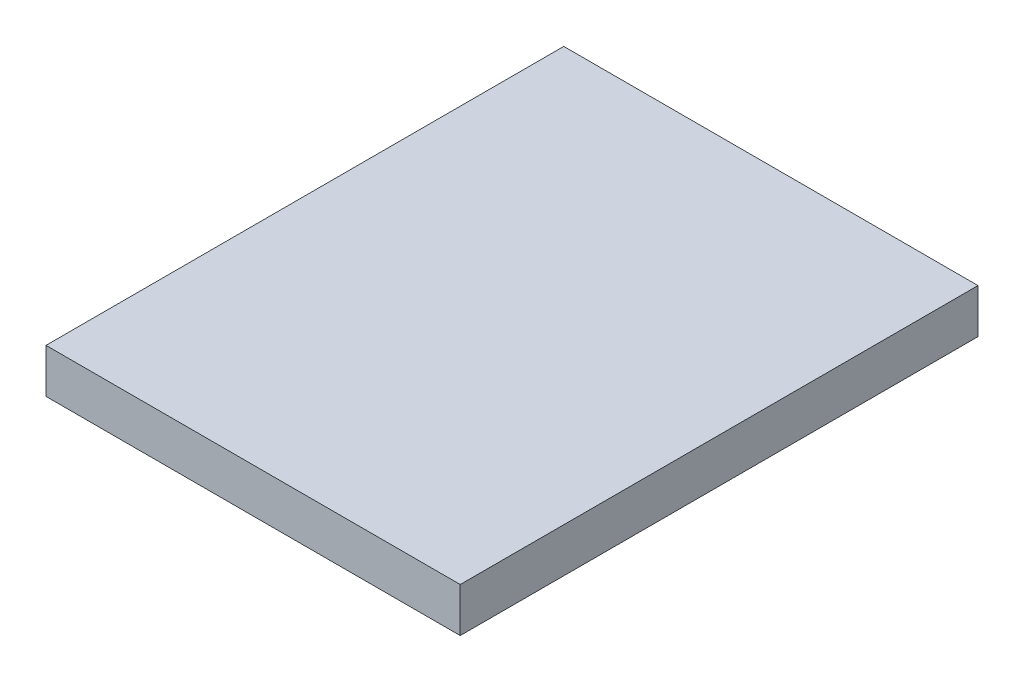
SolidWorks part; units mm, degrees
ref_plane "Front Plane" through (0, 0, 0) normal (0, 0, 1) x (1, 0, 0)
ref_plane "Top Plane" through (0, 0, 0) normal (0, 1, 0) x (1, 0, 0)
ref_plane "Right Plane" through (0, 0, 0) normal (1, 0, 0) x (0, 0, -1)
sketch "Sketch2" plane through (0, 0, 0) normal (0, 1, 0) x (1, 0, 0)
  line L1 (22, -27.5) -> (-22, -27.5)
  line L2 (22, -27.5) -> (22, 27.5)
  line L3 (22, 27.5) -> (-22, 27.5)
  line L4 (-22, -27.5) -> (-22, 27.5)
  line L5 (22, -27.5) -> (-22, 27.5) construction
  line L6 (22, 27.5) -> (-22, -27.5) construction
  point P0 (0, 0)
  dimension "D1" = 44
  dimension "D2" = 55
extrude "Boss-Extrude1" add sketch "Sketch2" along normal blind 4.7
sketch "Sketch3" plane through (0, 4.7, 0) normal (0, 1, 0) x (1, 0, 0)
  text T0 "Raspberry Pi \r\nModule" font "Century Gothic" height in points 20
